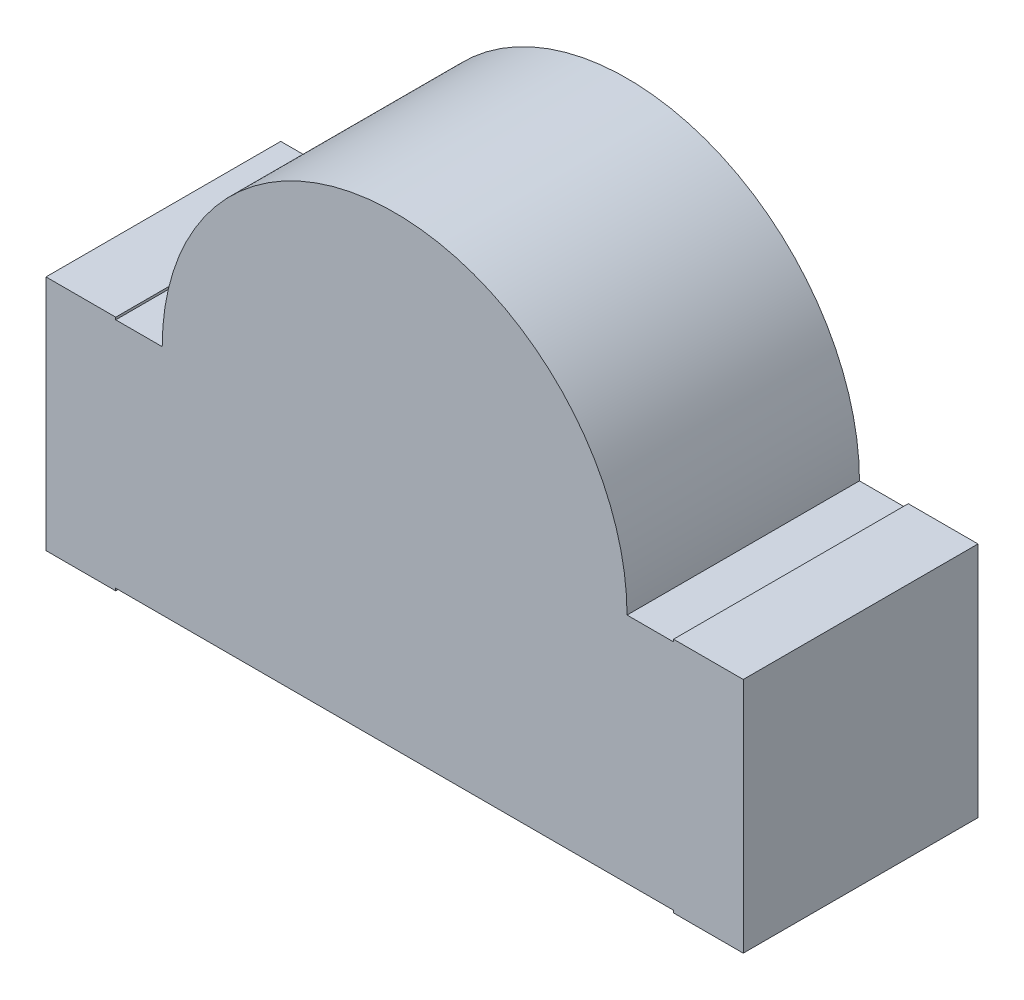
SolidWorks part; units mm, degrees
ref_plane "前视基准面" through (0, 0, 0) normal (0, 0, 1) x (1, 0, 0)
ref_plane "上视基准面" through (0, 0, 0) normal (0, 1, 0) x (1, 0, 0)
ref_plane "右视基准面" through (0, 0, 0) normal (1, 0, 0) x (0, 0, -1)
sketch "草图1" plane through (0, 0, 0) normal (0, 0, 1) x (1, 0, 0)
  line L0 (2.5, 1) -> (3, 1)
  line L1 (0, 0) -> (3, 0)
  line L2 (0, 0) -> (0, 1)
  line L3 (0, 1) -> (0.5, 1)
  line L4 (3, 0) -> (3, 1)
  line L5 (1.5, 2.449) -> (1.5, -0.5384) construction
  arc A0 (2.5, 1) -> (0.5, 1) centre (1.5, 1) ccw
  dimension "D3" = 2
  dimension "D1" = 1
  dimension "D2" = 3
extrude "凸台-拉伸1" add sketch "草图1" along normal blind 1
sketch "草图2" plane through (0, 0, 0) normal (0, -1, 0) x (1, 0, 0)
  line L0 (-0.1307, 0.5) -> (3.2138, 0.5) construction
  line L1 (0, 0) -> (3, 0) construction
  line L2 (0, 1) -> (3, 1) construction
  line L3 (2.2, 0.821) -> (2.2, 0.179)
  line L4 (2.2, 0.179) -> (1.644, 0.5)
  line L5 (1.644, 0.5) -> (2.2, 0.821)
  line L6 (3, 1) -> (3, 0) construction
  dimension "D1" = 0.8
  dimension "D2" = 0.6421
split line "分割线1"
sketch "草图3" plane through (3, 0, 0) normal (1, 0, 0) x (0, 0, -1)
  line L0 (-1.208, 0.5) -> (0.2443, 0.5) construction
  line L1 (-1, -0.01) -> (0.01, -0.01)
  line L2 (-1, -0.01) -> (-1, 1.01)
  line L3 (-1, 1.01) -> (0.01, 1.01)
  line L4 (0.01, -0.01) -> (0.01, 1.01)
  line L5 (-0.5, -0.1578) -> (-0.5, 2.2705) construction
  line L6 (-1, 0) -> (-1, 1) construction
  line L7 (0, 0) -> (0, 1) construction
  line L8 (-1, 0) -> (0, 0) construction
  line L9 (-1, 1) -> (0, 1) construction
  dimension "D1" = 1.01
  dimension "D2" = 1.02
extrude "凸台-拉伸2" add sketch "草图3" against normal blind 0.3
sketch "草图4" plane through (0, 0, 0) normal (-1, 0, 0) x (0, 0, 1)
  line L0 (-0.01, -0.01) -> (-0.01, 1.01) construction
  line L1 (1, -0.01) -> (-0.01, -0.01) construction
  line L2 (1, 0) -> (1, -0.01) construction
  line L3 (-0.01, -0.01) -> (-0.01, 1.01)
  line L4 (1, -0.01) -> (-0.01, -0.01)
  line L5 (1, 0) -> (1, -0.01)
  line L6 (-0.01, 1.01) -> (1, 1.01)
  line L7 (1, 1.01) -> (1, 0)
extrude "凸台-拉伸3" add sketch "草图4" against normal blind 0.3
